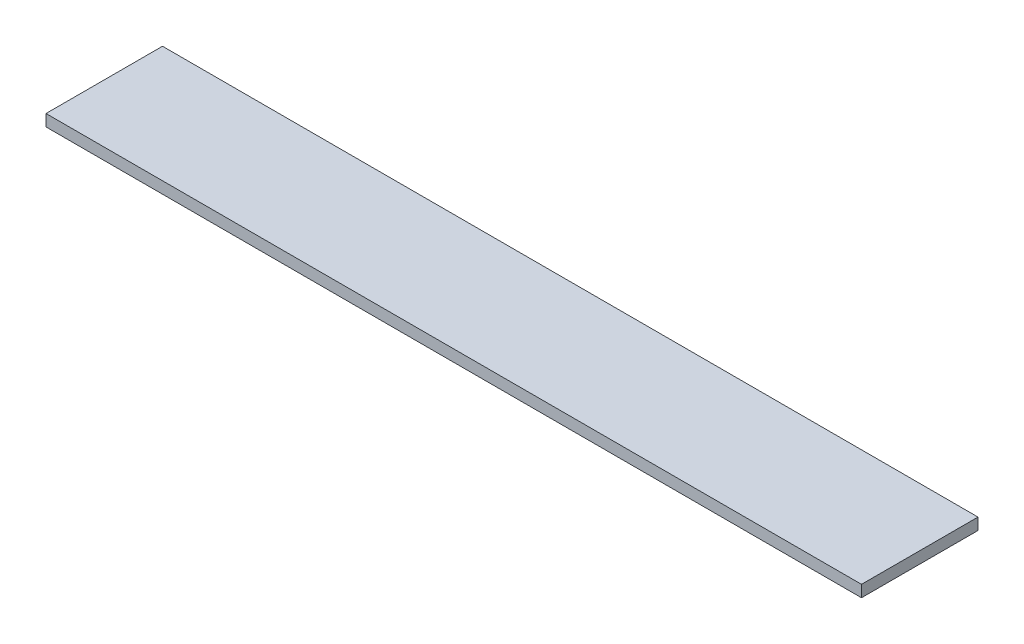
SolidWorks part; units mm, degrees
material "Rubber"
ref_plane "Front Plane" through (0, 0, 0) normal (0, 0, 1) x (1, 0, 0)
ref_plane "Top Plane" through (0, 0, 0) normal (0, 1, 0) x (1, 0, 0)
ref_plane "Right Plane" through (0, 0, 0) normal (1, 0, 0) x (0, 0, -1)
sketch "Sketch1" plane through (0, 0, 0) normal (0, 1, 0) x (1, 0, 0)
  line L0 (-3500, -500) -> (3500, 500) construction
  line L1 (-3500, 500) -> (3500, 500)
  line L2 (-3500, 500) -> (-3500, -500)
  line L3 (-3500, -500) -> (3500, -500)
  line L4 (3500, 500) -> (3500, -500)
  dimension "D1" = 1000
  dimension "D2" = 7000
extrude "Extrude1" add sketch "Sketch1" along normal blind 100
